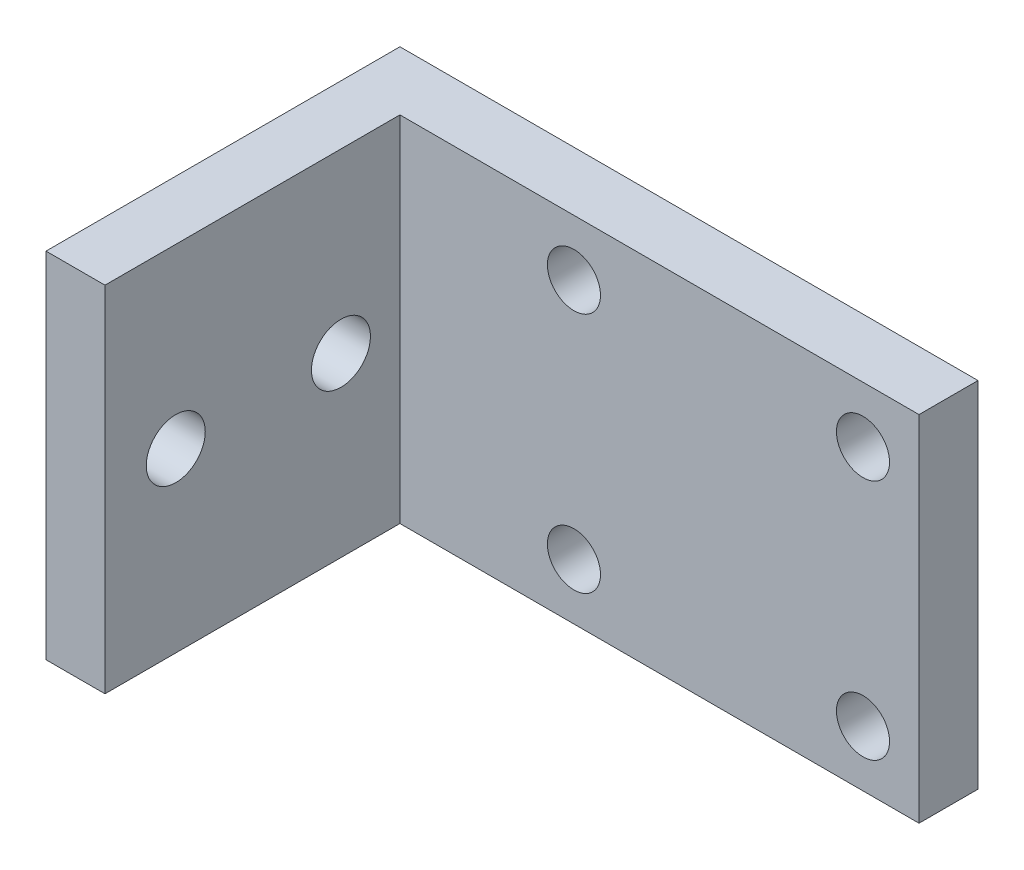
SolidWorks part; units mm, degrees
ref_plane "Front Plane" through (0, 0, 0) normal (0, 0, 1) x (1, 0, 0)
ref_plane "Top Plane" through (0, 0, 0) normal (0, 1, 0) x (1, 0, 0)
ref_plane "Right Plane" through (0, 0, 0) normal (1, 0, 0) x (0, 0, -1)
sketch "Sketch1" plane through (0, 0, 0) normal (0, 0, 1) x (1, 0, 0)
  line L1 (0, 0) -> (34, 0)
  line L2 (0, 0) -> (0, 30)
  line L3 (0, 30) -> (34, 30)
  line L4 (34, 0) -> (34, 30)
  circle A0 centre (4.75, 25.25) radius 2.25
  circle A1 centre (29.25, 25.25) radius 2.25
  circle A2 centre (29.25, 4.75) radius 2.25
  circle A3 centre (4.75, 4.75) radius 2.25
  dimension "D3" = 4.5
  dimension "D6" = 4.5
  dimension "D13" = 4.5
  dimension "D14" = 4.5
  dimension "D1" = 30
  dimension "D2" = 34
  dimension "D4" = 4.75
  dimension "D5" = 4.75
  dimension "D7" = 4.75
  dimension "D8" = 4.75
  dimension "D9" = 4.75
  dimension "D10" = 4.75
  dimension "D11" = 4.75
  dimension "D12" = 4.75
extrude "Boss-Extrude1" add sketch "Sketch1" along normal blind 5
sketch "Sketch2" plane through (0, 0, 0) normal (-1, 0, 0) x (0, 0, 1)
  line L1 (0, 30) -> (5, 30)
  line L2 (0, 30) -> (0, 0)
  line L3 (0, 0) -> (5, 0)
  line L4 (5, 30) -> (5, 0)
extrude "Boss-Extrude2" add sketch "Sketch2" along normal blind 15
sketch "Sketch3" plane through (0, 0, 5) normal (0, 0, 1) x (1, 0, 0)
  line L1 (0, 0) -> (-15, 0)
  line L2 (0, 0) -> (0, 30)
  line L3 (0, 30) -> (-15, 30)
  line L4 (-15, 0) -> (-15, 30)
sketch "Sketch4" plane through (0, 0, 5) normal (0, 0, 1) x (1, 0, 0)
  line L0 (0, 30) -> (-15, 30) construction
  line L1 (-15, 0) -> (-10, 0)
  line L2 (-15, 0) -> (-15, 30)
  line L3 (-15, 30) -> (-10, 30)
  line L4 (-10, 0) -> (-10, 30)
  dimension "D1" = 5
extrude "Boss-Extrude3" add sketch "Sketch4" along normal blind 25
sketch "Sketch5" plane through (-10, 0, 0) normal (1, 0, 0) x (0, 0, -1)
  line L1 (-30, 30) -> (-5, 30) construction
  line L2 (-30, 0) -> (-30, 30) construction
  circle A0 centre (-24, 15) radius 2.5
  circle A1 centre (-10, 15) radius 2.5
  dimension "D1" = 5
  dimension "D2" = 5
  dimension "D3" = 15
  dimension "D4" = 15
  dimension "D5" = 6
  dimension "D6" = 14
extrude "Cut-Extrude1" cut sketch "Sketch5" against normal blind 25
